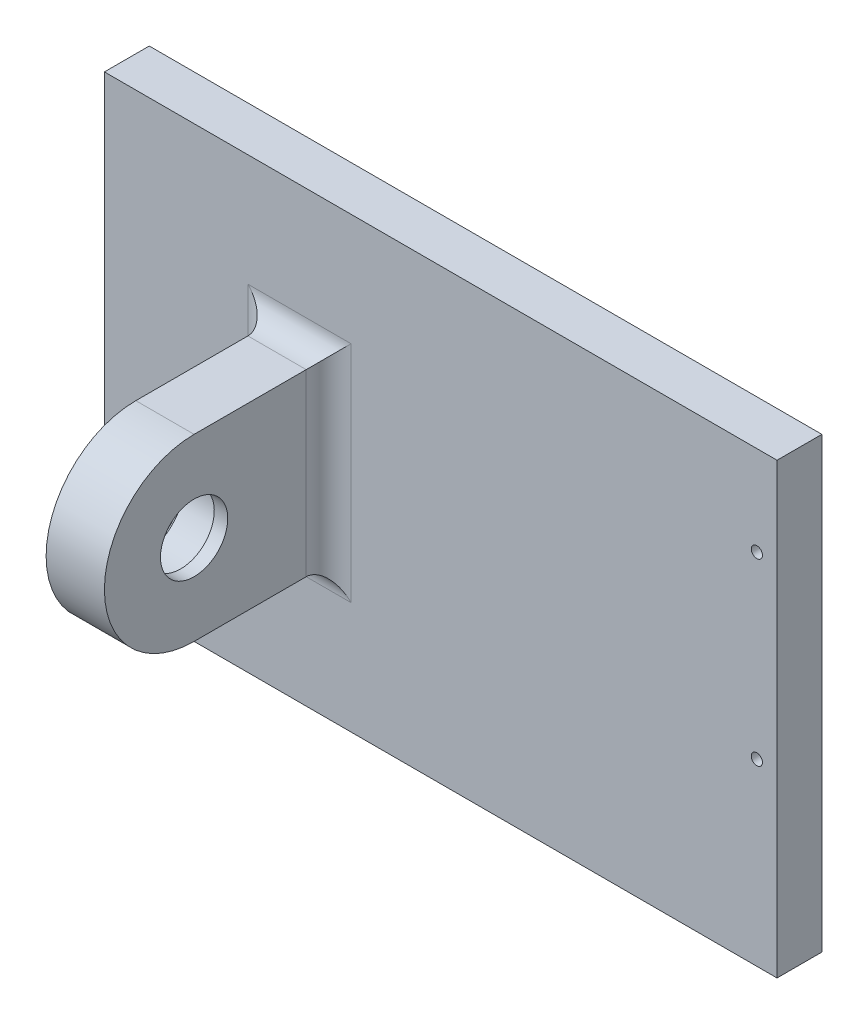
SolidWorks part; units mm, degrees
ref_plane "正面" through (0, 0, 0) normal (0, 0, 1) x (1, 0, 0)
ref_plane "平面" through (0, 0, 0) normal (0, 1, 0) x (1, 0, 0)
ref_plane "右側面" through (0, 0, 0) normal (1, 0, 0) x (0, 0, -1)
sketch "ｽｹｯﾁ2" plane through (0, 0, 0) normal (0, 0, 1) x (1, 0, 0)
  line L1 (-75, 50) -> (75, 50)
  line L2 (-75, 50) -> (-75, -50)
  line L3 (-75, -50) -> (75, -50)
  line L4 (75, 50) -> (75, -50)
  line L5 (-75, 50) -> (75, -50) construction
  line L6 (-75, -50) -> (75, 50) construction
  point P0 (0, 0)
  dimension "D1" = 150
  dimension "D2" = 100
extrude "ﾎﾞｽ - 押し出し1" add sketch "ｽｹｯﾁ2" along normal blind 10
sketch "ｽｹｯﾁ3" plane through (0, 0, 0) normal (0, 0, 1) x (1, 0, 0)
  line L0 (-38, 20) -> (-38, -20)
  line L1 (-38, -20) -> (-25, -20)
  line L2 (-25, -20) -> (-25, 20)
  line L3 (-25, 20) -> (-38, 20)
  dimension "D1" = 13
  dimension "D2" = 20
  dimension "D3" = 20
  dimension "D4" = 25
extrude "ﾎﾞｽ - 押し出し2" add sketch "ｽｹｯﾁ3" along normal blind 40
ref_plane "平面1" through (-38, 0, 0) normal (-1, 0, 0) x (0, 0, 1)
sketch "ｽｹｯﾁ4" plane through (-38, 0, 0) normal (-1, 0, 0) x (0, 0, 1)
  line L0 (40, 20) -> (40, -20) construction
  circle A0 centre (40, 0) radius 20
extrude "ﾎﾞｽ - 押し出し3" add sketch "ｽｹｯﾁ4" against normal blind 13
sketch "ｽｹｯﾁ5" plane through (-38, 0, 0) normal (-1, 0, 0) x (0, 0, 1)
  circle A0 centre (40, 0) radius 10
  dimension "D1" = 20
extrude "ｶｯﾄ - 押し出し1" cut sketch "ｽｹｯﾁ5" against normal blind 10
hole_wizard "M3x0.5 ねじ穴2" positions "ｽｹｯﾁ10" profile "ｽｹｯﾁ11" tap size "M3x0.5" standard "JIS" end condition through all
sketch "ｽｹｯﾁ10" plane through (0, 0, 10) normal (0, 0, 1) x (1, 0, 0)
  point P0 (70.5, -10.0009)
  point P3 (70.5, 29.9991)
sketch "ｽｹｯﾁ11" plane through (70.5, -10.0009, 10) normal (1, 0, 0) x (0, -1, 0)
  line L0 (0, 0) -> (0, 10)
  line L1 (0, 10) -> (1.25, 10)
  line L2 (1.25, 10) -> (1.25, 0)
  line L5 (1.25, 0) -> (0, 0)
  line L11 (0, -6.35) -> (0, 107.95) construction
  dimension "次ｻｰﾌｪｽまでのねじ下穴ﾄﾞﾘﾙ直径" = 2.5
  dimension "次ｻｰﾌｪｽまでのねじ下穴ﾄﾞﾘﾙの深さ" = 10
cosmetic thread "穴のねじ山4" parameters "D2"=3
cosmetic thread "穴のねじ山5" parameters "D2"=3
fillet "ﾌｨﾚｯﾄ1" radius 5 4 edges at (-31.5, -20, 10) (-38, 0, 10) (-31.5, 20, 10) (-25, 0, 10)
sketch "ｽｹｯﾁ12" plane through (-28, 0, 0) normal (-1, 0, 0) x (0, 0, 1)
  circle A0 centre (40, 0) radius 7.5
  dimension "D1" = 15
extrude "ｶｯﾄ - 押し出し2" cut sketch "ｽｹｯﾁ12" against normal through all
chamfer "面取り1" distance 1 angle 45 1 edges at (-38, -10, 40)
